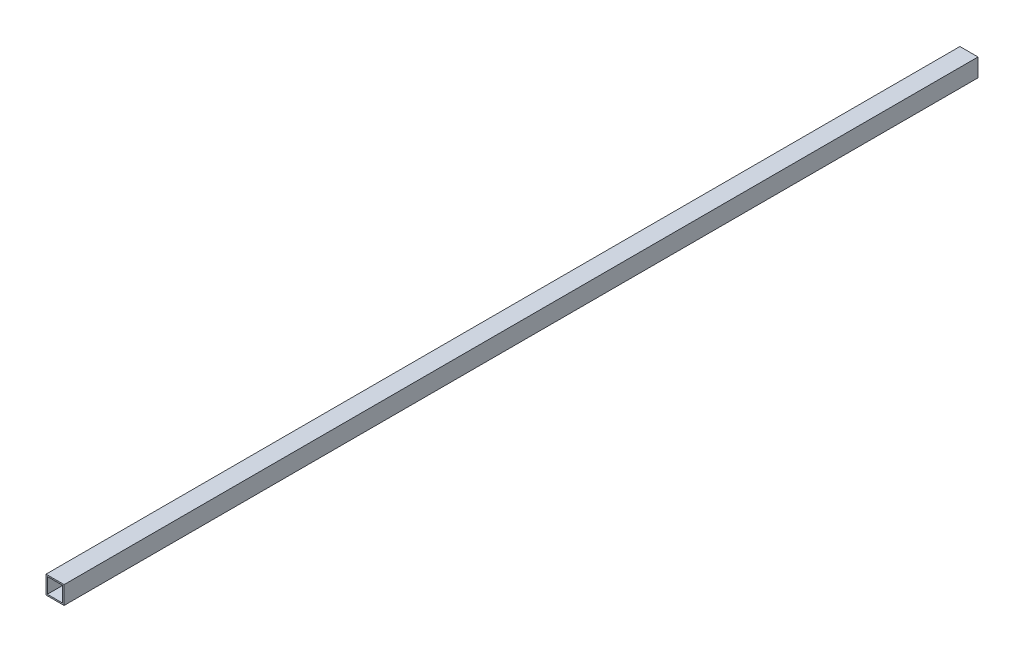
SolidWorks part; units mm, degrees
ref_plane "Спереди" through (0, 0, 0) normal (0, 0, 1) x (1, 0, 0)
ref_plane "Сверху" through (0, 0, 0) normal (0, 1, 0) x (1, 0, 0)
ref_plane "Справа" through (0, 0, 0) normal (1, 0, 0) x (0, 0, -1)
sketch "Эскиз1" plane through (0, 0, 0) normal (0, 0, 1) x (1, 0, 0)
  line L0 (-17, 17) -> (17, 17)
  line L1 (-20, 20) -> (20, 20)
  line L2 (-20, 20) -> (-20, -20)
  line L3 (-20, -20) -> (20, -20)
  line L4 (20, 20) -> (20, -20)
  line L5 (-20, 20) -> (20, -20) construction
  line L6 (-20, -20) -> (20, 20) construction
  line L7 (17, 17) -> (17, -17)
  line L8 (-17, -17) -> (17, -17)
  line L9 (-17, 17) -> (-17, -17)
  point P0 (0, 0)
  dimension "D1" = 40
  dimension "D2" = 40
  dimension "D3" = 3
extrude "Бобышка-Вытянуть1" add sketch "Эскиз1" along normal blind 2020
sketch "Эскиз2" plane through (0, -20, 0) normal (0, -1, 0) x (-1, 0, 0)
  line L0 (0, 0) -> (0, -20) construction
  circle A0 centre (0, -20) radius 7
  dimension "D2" = 14
  dimension "D1" = 20
extrude "Вырез-Вытянуть1" [suppressed] cut sketch "Эскиз2" against normal through all
sketch "Эскиз3" [suppressed] plane through (0, -20, 0) normal (0, -1, 0) x (-1, 0, 0)
  circle A0 centre (0, -20) radius 9.5
  dimension "D1" = 19
extrude "Вырез-Вытянуть2" [suppressed] cut sketch "Эскиз3" against normal blind 10
